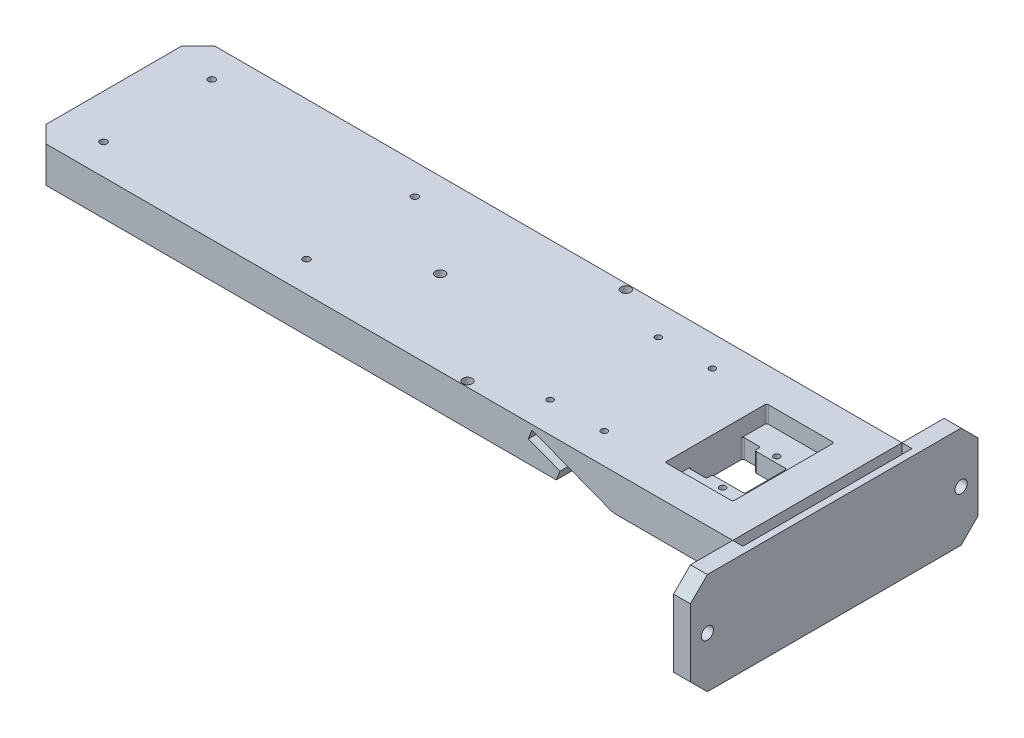
SolidWorks part; units mm, degrees
ref_plane "Front Plane" through (0, 0, 0) normal (0, 0, 1) x (1, 0, 0)
ref_plane "Top Plane" through (0, 0, 0) normal (0, 1, 0) x (1, 0, 0)
ref_plane "Right Plane" through (0, 0, 0) normal (1, 0, 0) x (0, 0, -1)
sketch "Sketch1" plane through (0, 0, 0) normal (0, 0, 1) x (1, 0, 0)
  line L0 (-9.3358, 3.5837) -> (0, 0)
  line L1 (0, 0) -> (-2, 0) construction
  line L3 (-9.3358, 3.5837) -> (-10.4109, 0.7829)
  line L4 (-10.4109, 0.7829) -> (-1.0751, -2.8007)
  line L5 (-1.0751, -2.8007) -> (-2.1502, -5.6015)
  line L9 (-18, 5) -> (0, 5)
  line L10 (-1.0751, -2.8007) -> (0, 0) construction
  line L11 (0, 5) -> (50, 5)
  line L12 (50, 5) -> (50, -25)
  line L13 (-18, 5) -> (-158, 5)
  line L15 (-2.1502, -5.6015) -> (-158, -5.6015)
  line L16 (-158, 5) -> (-158, -5.6015)
  line L17 (50, -25) -> (45, -25)
  line L20 (14.5924, -5.6015) -> (0, 0)
  line L21 (14.5924, -5.6015) -> (45, -5.6015)
  line L22 (45, -5.6015) -> (45, -25)
  dimension "D1" = 21
  dimension "D2" = 2
  dimension "D3" = 10
  dimension "D4" = 3
  dimension "D5" = 3
  dimension "D6" = 5
  dimension "D7" = 18
  dimension "D8" = 140
  dimension "D9" = 50
  dimension "D10" = 5
  dimension "D11" = 30
extrude "Boss-Extrude1" add sketch "Sketch1" along normal blind 50
sketch "Sketch3" plane through (50, 0, 0) normal (1, 0, 0) x (0, 0, -1)
  line L0 (17.5, 5) -> (-67.5, 5)
  line L2 (-67.5, 5) -> (-67.5, -25)
  line L3 (-67.5, -25) -> (17.5, -25)
  line L4 (17.5, -25) -> (17.5, 5)
  line L5 (-50, 5) -> (0, 5) construction
  line L6 (-50, -25) -> (0, -25) construction
  line L7 (17.5, -10) -> (-67.5, -10) construction
  line L8 (12.5, -10) -> (-62.5, -10) construction
  circle A0 centre (-62.5, -10) radius 1.8
  circle A1 centre (12.5, -10) radius 1.8
  point P3 (-25, 5)
  point P17 (-25, -10)
  point P18 (-25, -10)
  dimension "D3" = 3.6
  dimension "D1" = 85
  dimension "D2" = 75
extrude "Boss-Extrude2" add sketch "Sketch3" along normal blind 5 separate body
sketch "Sketch4" plane through (50, 0, 0) normal (-1, 0, 0) x (0, 0, 1)
  line L0 (50, 5) -> (0, 5) construction
  line L1 (50, -25) -> (50, 5) construction
  line L2 (50, -25) -> (0, -25) construction
  line L3 (0, -25) -> (0, 5) construction
  line L4 (50, 5) -> (0, 5)
  line L5 (50, -25) -> (50, 5)
  line L6 (50, -25) -> (0, -25)
  line L7 (0, -25) -> (0, 5)
extrude "Cut-Extrude1" cut sketch "Sketch4" against normal blind 3
sketch "Sketch5" plane through (0, 5, 0) normal (0, 1, 0) x (1, 0, 0)
  line L0 (50, -25) -> (-158, -25) construction
  line L1 (50, -50) -> (50, 0) construction
  line L2 (-158, -50) -> (-158, 0) construction
  line L3 (-30, -1.6) -> (-30, -48.4) construction
  line L4 (-13, -41) -> (3, -41) construction
  line L5 (-13, -41) -> (-13, -9) construction
  line L6 (-13, -9) -> (3, -9) construction
  line L7 (3, -41) -> (3, -9) construction
  line L8 (-13, -41) -> (3, -9) construction
  line L9 (-13, -9) -> (3, -41) construction
  line L11 (20, -40) -> (40, -40)
  line L12 (20, -40) -> (20, -10)
  line L13 (20, -10) -> (40, -10)
  line L14 (40, -40) -> (40, -10)
  line L15 (20, -40) -> (40, -10) construction
  line L16 (20, -10) -> (40, -40) construction
  circle A0 centre (3, -9) radius 0.9
  circle A1 centre (-13, -9) radius 0.9
  circle A2 centre (-13, -41) radius 0.9
  circle A3 centre (3, -41) radius 0.9
  circle A4 centre (-30, -1.6) radius 1.4
  circle A5 centre (-30, -48.4) radius 1.4
  circle A6 centre (-61.5, -25) radius 1.4
  point P8 (-5, -25)
  point P18 (-30, -25)
  point P22 (30, -25)
  dimension "D1" = 1.8
  dimension "D6" = 2.8
  dimension "D2" = 55
  dimension "D3" = 32
  dimension "D4" = 16
  dimension "D5" = 46.8
  dimension "D7" = 31.5
  dimension "D8" = 80
  dimension "D9" = 20
  dimension "D10" = 30
  dimension "D11" = 20
extrude "Cut-Extrude2" cut sketch "Sketch5" against normal blind 5
sketch "Sketch7" plane through (0, 0, 0) normal (0, 1, 0) x (1, 0, 0)
  line L0 (30, -10) -> (30, -40) construction
  line L1 (40, -10) -> (20, -10) construction
  line L2 (20, -40) -> (40, -40) construction
  line L3 (30, -17) -> (30, -33) construction
  line L4 (20, -10) -> (20, -40) construction
  line L5 (25.25, -18.75) -> (34.75, -18.75)
  line L6 (25.25, -18.75) -> (25.25, -31.25)
  line L7 (25.25, -31.25) -> (34.75, -31.25)
  line L8 (34.75, -18.75) -> (34.75, -31.25)
  line L9 (25.25, -18.75) -> (34.75, -31.25) construction
  line L10 (25.25, -31.25) -> (34.75, -18.75) construction
  line L11 (25.25, -17) -> (20, -17)
  line L12 (25.25, -17) -> (25.25, -33)
  line L13 (25.25, -33) -> (20, -33)
  line L14 (20, -17) -> (20, -33)
  circle A0 centre (30, -17) radius 0.9
  circle A1 centre (30, -33) radius 0.9
  point P11 (30, -25)
  point P14 (30, -25)
  point P21 (25.25, -25)
  line M10 (20, -10) -> (20, -40)
  dimension "D2" = 1.8
  dimension "D3" = 9.5
  dimension "D1" = 16
  dimension "D4" = 12.5
  dimension "D5" = 16
extrude "Cut-Extrude4" cut sketch "Sketch7" along direction (0, 1, 0) on the side against the normal up to surface (5.6015 mm away) contours L13 L12 L6 L11 M10 | L8 L5 L6 L7 | A0 | A1
sketch "Sketch8" plane through (0, 5, 0) normal (0, 1, 0) x (1, 0, 0)
  line L0 (50, -25) -> (-85, -25) construction
  line L1 (-145, -9) -> (-85, -9) construction
  line L2 (-145, -9) -> (-145, -41) construction
  line L3 (-145, -41) -> (-85, -41) construction
  line L4 (-85, -9) -> (-85, -41) construction
  line L5 (50, -50) -> (50, 0) construction
  circle A0 centre (-85, -41) radius 1
  circle A1 centre (-85, -9) radius 1
  circle A2 centre (-145, -9) radius 1
  circle A3 centre (-145, -41) radius 1
  dimension "D4" = 2
  dimension "D1" = 32
  dimension "D2" = 60
  dimension "D3" = 135
extrude "Cut-Extrude5" cut sketch "Sketch8" against normal up to surface (10.6015 mm away) up to face at (-80.0751, -5.6015, 25)
fillet "Fillet2" radius 0.5 12 edges at (20, -2.8007, 33) (20, -2.8007, 17) (25.25, -2.8007, 17) (25.25, -2.8007, 18.75) (25.25, -2.8007, 33) (25.25, -2.8007, 31.25) (34.75, -2.8007, 31.25) (34.75, -2.8007, 18.75) (20, 2.5, 10) (40, 2.5, 40) (20, 2.5, 40) (40, 2.5, 10)
chamfer "Chamfer1" distance 5 angle 45 4 edges at (52.5, 5, -17.5) (52.5, -25, -17.5) (52.5, -25, 67.5) (52.5, 5, 67.5)
fillet "Fillet1" radius 5 2 edges at (45, -5.6015, 25) (14.5924, -5.6015, 25)
chamfer "Chamfer2" distance 5 angle 45 2 edges at (-158, -0.3007, 50) (-158, -0.3007, 0)
